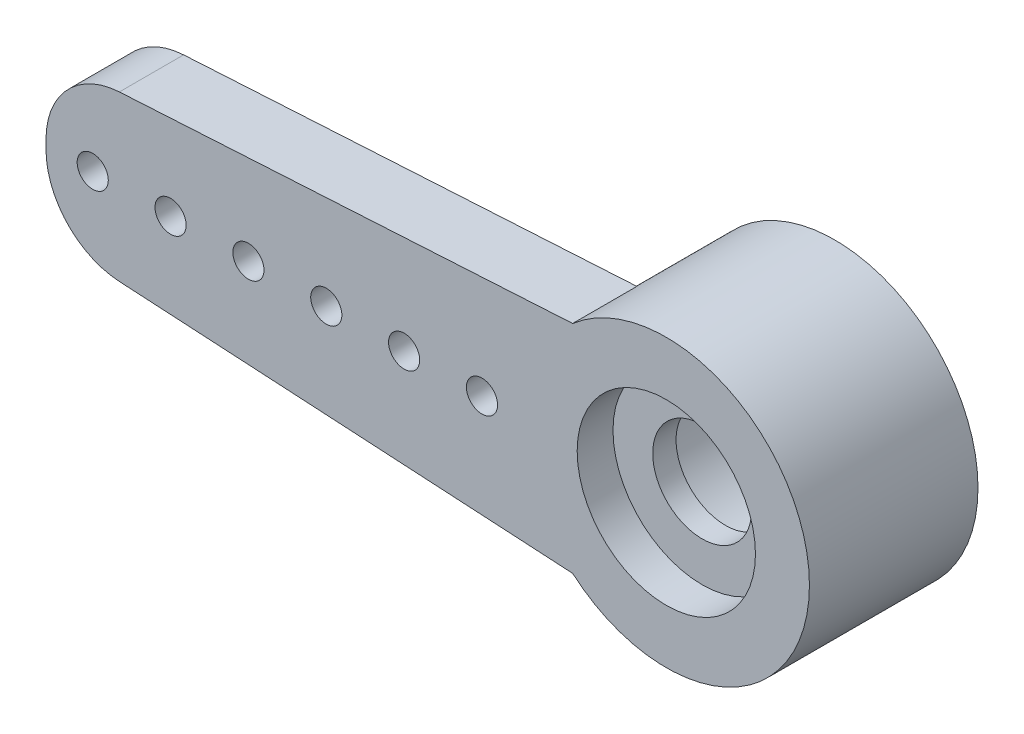
SolidWorks part; units mm, degrees
ref_plane "Front Plane" through (0, 0, 0) normal (0, 0, 1) x (1, 0, 0)
ref_plane "Top Plane" through (0, 0, 0) normal (0, 1, 0) x (1, 0, 0)
ref_plane "Right Plane" through (0, 0, 0) normal (1, 0, 0) x (0, 0, -1)
sketch "Sketch1" plane through (0, 0, 0) normal (0, 0, 1) x (1, 0, 0)
  circle A0 centre (0, 0) radius 3.6766
  dimension "D1" = 7.3533
extrude "Boss-Extrude1" add sketch "Sketch1" along normal blind 4.33 contours A0
sketch "Sketch2" plane through (0, 0, 0) normal (0, 0, -1) x (-1, 0, 0)
  circle A0 centre (0, 0) radius 2.235
  dimension "D1" = 4.47
extrude "Cut-Extrude1" cut sketch "Sketch2" against normal blind 2.81
sketch "Sketch3" plane through (0, 0, 4.33) normal (0, 0, 1) x (1, 0, 0)
  circle A0 centre (0, 0) radius 2.29
  dimension "D1" = 4.58
extrude "Cut-Extrude2" cut sketch "Sketch3" against normal blind 0.92
sketch "Sketch4" plane through (0, 0, 3.41) normal (0, 0, 1) x (1, 0, 0)
  circle A0 centre (0, 0) radius 1.27
  dimension "D1" = 2.54
extrude "Cut-Extrude3" cut sketch "Sketch4" against normal through all
sketch "Sketch5" plane through (0, 0, 4.33) normal (0, 0, 1) x (1, 0, 0)
  line L0 (-2.4061, 2.78) -> (-15.935, 2)
  line L1 (-15.935, 2) -> (-15.935, -2)
  line L2 (-15.935, -2) -> (-2.4061, -2.78)
  line L3 (0, 0) -> (-15.935, 0) construction
  line L4 (-2.4061, -2.78) -> (-2.4061, 0) construction
  line L5 (-2.4061, 2.78) -> (-2.4061, 0) construction
  circle A0 centre (0, 0) radius 3.6766 construction
  circle A1 centre (0, 0) radius 3.6766
  circle A2 centre (0, 0) radius 3.6766
  circle M3 centre (0, 0) radius 3.6766
  dimension "D2" = 5.56
  dimension "D3" = 15.935
  dimension "D4" = 4
  dimension "D1" = 0
extrude "Boss-Extrude2" add sketch "Sketch5" against normal blind 1.65 contours L1 L2 L0 M3
fillet "Fillet1" radius 2 2 edges at (-15.935, -2, 3.505) (-15.935, 2, 3.505)
sketch "Sketch6" plane through (0, 0, 4.33) normal (0, 0, 1) x (1, 0, 0)
  line L0 (0, 0) -> (-15.935, 0) construction
  line L1 (-15.935, 0.112) -> (-15.935, -0.112) construction
  line L2 (-12.735, 0) -> (-14.735, 0) construction
  circle A0 centre (-14.735, 0) radius 0.4
  circle A1 centre (-12.735, 0) radius 0.4
  circle A2 centre (-10.735, 0) radius 0.4
  circle A3 centre (-8.735, 0) radius 0.4
  circle A4 centre (-6.735, 0) radius 0.4
  circle A5 centre (-4.735, 0) radius 0.4
  dimension "D2" = 0.8
  dimension "D1" = 1.2
  dimension "D3" = 2
  dimension "D4" = 2
  dimension "D5" = 2
  dimension "D6" = 2
  dimension "D7" = 2
extrude "Cut-Extrude4" cut sketch "Sketch6" against normal through all
equation "\"hole_space\"=2"
equation "\"D3@Sketch6\"=\"hole_space\""
equation "\"D4@Sketch6\"=\"hole_space\""
equation "\"D5@Sketch6\"=\"hole_space\""
equation "\"D6@Sketch6\"=\"hole_space\""
equation "\"D7@Sketch6\"=\"hole_space\""
